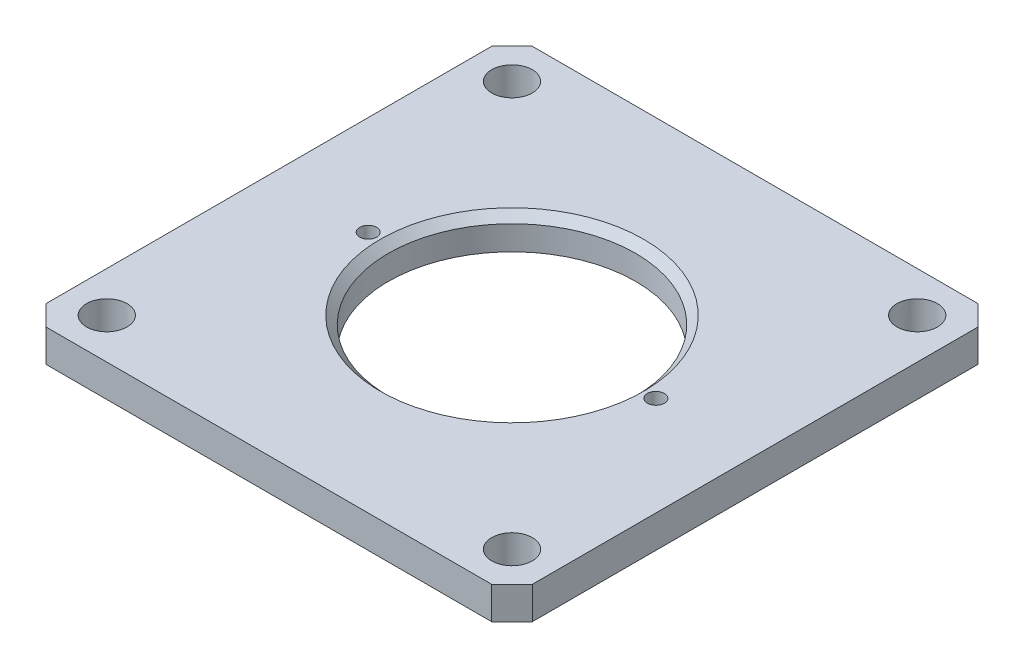
SolidWorks part; units mm, degrees
material "AU4G - 2017A"
ref_plane "Plan de face" through (0, 0, 0) normal (0, 0, 1) x (1, 0, 0)
ref_plane "Plan de dessus" through (0, 0, 0) normal (0, 1, 0) x (1, 0, 0)
ref_plane "Plan de droite" through (0, 0, 0) normal (1, 0, 0) x (0, 0, -1)
sketch "Sketch1" plane through (0, 0, 0) normal (0, 1, 0) x (1, 0, 0)
  line L0 (-60, -60) -> (60, 60) construction
  line L1 (-60, -60) -> (60, -60)
  line L2 (-60, -60) -> (-60, 60)
  line L3 (-60, 60) -> (60, 60)
  line L4 (60, -60) -> (60, 60)
  point P4 (0, 0)
  dimension "D1" = 120
  dimension "D2" = 120
extrude "Boss-Extrude1" add sketch "Sketch1" along normal blind 8
sketch "Sketch2" plane through (0, 8, 0) normal (0, 1, 0) x (1, 0, 0)
  circle A0 centre (0, 0) radius 30.5
  dimension "D1" = 61
extrude "Cut-Extrude1" cut sketch "Sketch2" against normal up to next
chamfer "Chamfer1" distance 2 angle 45 1 edges at (0, 8, 30.5)
sketch "Sketch3" plane through (0, 8, 0) normal (0, 1, 0) x (1, 0, 0)
  line L0 (-60, 0) -> (-89.4469, 0) construction
  line L1 (-60, 60) -> (-60, -60) construction
  line L2 (0, -60) -> (0, -62.1463) construction
  line L3 (-60, -60) -> (60, -60) construction
  circle A0 centre (-50, 50) radius 5
  circle A1 centre (50, 50) radius 5
  circle A2 centre (-50, -50) radius 5
  circle A3 centre (50, -50) radius 5
  dimension "D3" = 10
  dimension "D1" = 10
  dimension "D2" = 10
extrude "Cut-Extrude2" cut sketch "Sketch3" against normal up to next
chamfer "Chamfer2" distance 5 angle 45 4 edges at (60, 4, -60) (60, 4, 60) (-60, 4, -60) (-60, 4, 60)
hole_wizard "M5 Tapped Hole1" positions "Sketch5" profile "Sketch4" tap size "M5" standard "ISO" end condition through all
sketch "Sketch5" plane through (0, 8, 0) normal (0, 1, 0) x (1, 0, 0)
  circle A0 centre (0, 0) radius 35.5
  point P0 (-35.5, 0)
  point P2 (35.5, 0)
  dimension "D1" = 71
sketch "Sketch4" plane through (-35.5, 8, 0) normal (1, 0, 0) x (0, 0, 1)
  line L0 (0, 0) -> (0, 8)
  line L1 (0, 8) -> (2.1, 8)
  line L2 (2.1, 8) -> (2.1, 0)
  line L5 (2.1, 0) -> (0, 0)
  line L11 (0, -6.35) -> (0, 107.95) construction
  dimension "Thru Tap Drill Dia." = 4.2
  dimension "Thru Tap Drill Depth" = 8
cosmetic thread "Hole Thread1" parameters "D2"=5
cosmetic thread "Hole Thread2" parameters "D2"=5
